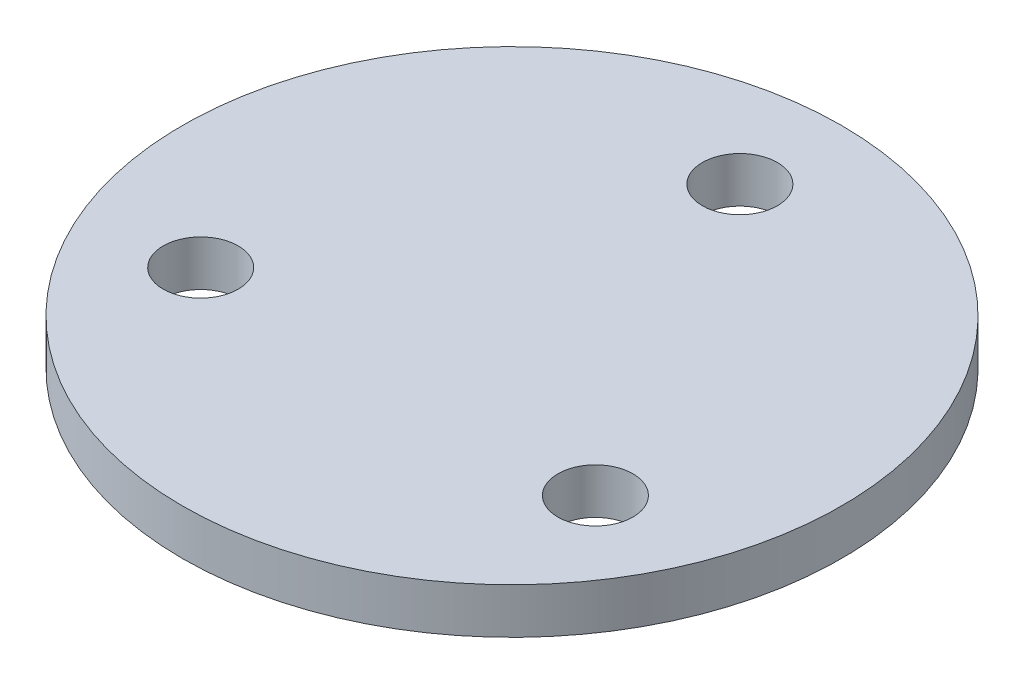
SolidWorks part; units mm, degrees
ref_plane "Front Plane" through (0, 0, 0) normal (0, 0, 1) x (1, 0, 0)
ref_plane "Top Plane" through (0, 0, 0) normal (0, 1, 0) x (1, 0, 0)
ref_plane "Right Plane" through (0, 0, 0) normal (1, 0, 0) x (0, 0, -1)
sketch "Sketch1" plane through (0, 0, 0) normal (0, 1, 0) x (1, 0, 0)
  circle A0 centre (0, 0) radius 11.938
  dimension "D1" = 23.876
extrude "Boss-Extrude1" add sketch "Sketch1" along normal blind 1.651
sketch "Sketch2" plane through (0, 1.651, 0) normal (0, 1, 0) x (1, 0, 0)
  circle A0 centre (0, 8.255) radius 1.3589
  dimension "D1" = 8.255
extrude "Cut-Extrude1" cut sketch "Sketch2" against normal blind 1.651
pattern_circular "CirPattern1" count 3 over 360 about axis through (0, 0, 0) along (0, 1, 0) of "Cut-Extrude1"
